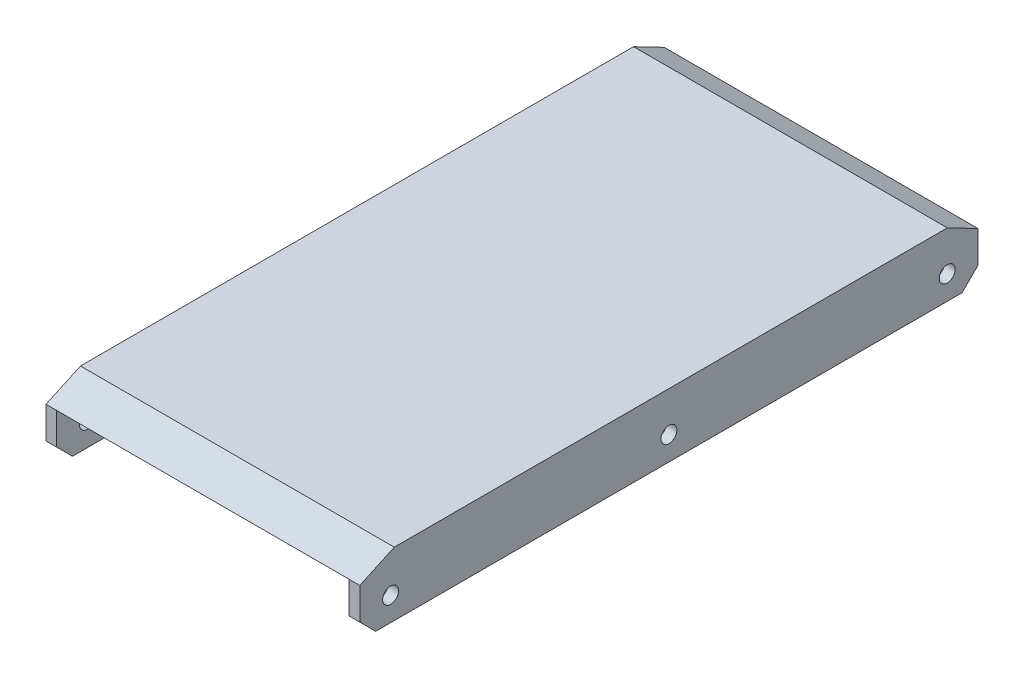
SolidWorks part; units mm, degrees
ref_plane "Front Plane" through (0, 0, 0) normal (0, 0, 1) x (1, 0, 0)
ref_plane "Top Plane" through (0, 0, 0) normal (0, 1, 0) x (1, 0, 0)
ref_plane "Right Plane" through (0, 0, 0) normal (1, 0, 0) x (0, 0, -1)
sketch "Sketch1" plane through (0, 0, 0) normal (1, 0, 0) x (0, 0, -1)
  line L0 (-58.31, 0) -> (58.31, 0)
  line L3 (-58.31, 0) -> (-51.8117, 3) construction
  line L4 (-51.8117, 3) -> (52.5257, 3) construction
  line L5 (58.31, 0) -> (52.5257, 3) construction
  line L6 (0, 0) -> (0, -9) construction
  line L7 (-58.31, -9) -> (58.31, -9)
  line L11 (-58.31, 0) -> (-58.31, -9)
  line L13 (58.31, 0) -> (58.31, -9)
  point P4 (0, 0)
  dimension "D1" = 116.62
  dimension "D4" = 3
  dimension "D5" = 9
extrude "Boss-Extrude1" add sketch "Sketch1" along normal blind 2
ref_plane "Plane1" through (57.2, 0, 0) normal (1, 0, 0) x (0, 0, -1)
sketch "Sketch6" plane through (0, 0, 0) normal (-1, 0, 0) x (0, 0, 1)
  line L0 (0, 0) -> (0, -9) construction
  line L1 (58.31, -9) -> (-58.31, -9) construction
  line L2 (-52.5, -4.5) -> (52.5, -4.5) construction
  circle A0 centre (0, -4.5) radius 1.5
  circle A1 centre (52.5, -4.5) radius 1.5
  circle A2 centre (-52.5, -4.5) radius 1.5
  point P10 (0, -4.5)
  dimension "D2" = 3
  dimension "D1" = 105
extrude "Cut-Extrude1" cut sketch "Sketch6" against normal through all
chamfer "Chamfer4" distance 3 angle 45 2 edges at (1, -9, 58.31) (1, -9, -58.31)
sketch "Sketch9" plane through (57.2, 0, 0) normal (1, 0, 0) x (0, 0, -1)
  line L6 (-58.31, 0) -> (-58.31, -6)
  line L7 (-58.31, -6) -> (-55.31, -9)
  line L8 (-55.31, -9) -> (55.31, -9)
  line L9 (55.31, -9) -> (58.31, -6)
  line L10 (58.31, -6) -> (58.31, 0)
  line L11 (58.31, 0) -> (-58.31, 0)
  line L12 (-58.31, 0) -> (-58.31, -6)
  line L13 (-58.31, -6) -> (-55.31, -9)
  line L14 (-55.31, -9) -> (55.31, -9)
  line L15 (55.31, -9) -> (58.31, -6)
  line L16 (58.31, -6) -> (58.31, 0)
  line L17 (58.31, 0) -> (-58.31, 0)
  circle A1 centre (0, -4.5) radius 1.5
  circle A2 centre (0, -4.5) radius 1.5
  circle A3 centre (-52.5, -4.5) radius 1.5
  circle A4 centre (-52.5, -4.5) radius 1.5
  circle A5 centre (52.5, -4.5) radius 1.5
  circle A6 centre (52.5, -4.5) radius 1.5
  dimension "D1" = 0
  dimension "D2" = 0
  dimension "D3" = 0
  dimension "D4" = 0
extrude "Boss-Extrude4" add sketch "Sketch9" along normal blind 2 separate body
sketch "Sketch4" plane through (2, 0, 0) normal (1, 0, 0) x (0, 0, -1)
  line L0 (-58.31, 0) -> (-51.8117, 3)
  line L1 (-51.8117, 3) -> (52.5257, 3)
  line L2 (52.5257, 3) -> (58.31, 0)
  line L3 (58.31, 0) -> (-58.31, 0)
extrude "Boss-Extrude5" add sketch "Sketch4" along normal up to surface (59.2 mm away) from surface at -2 contours L1 L2 L3 L0 up to face at (59.2, -4.5, 51) starting at face at (0, -4.5, -51)
